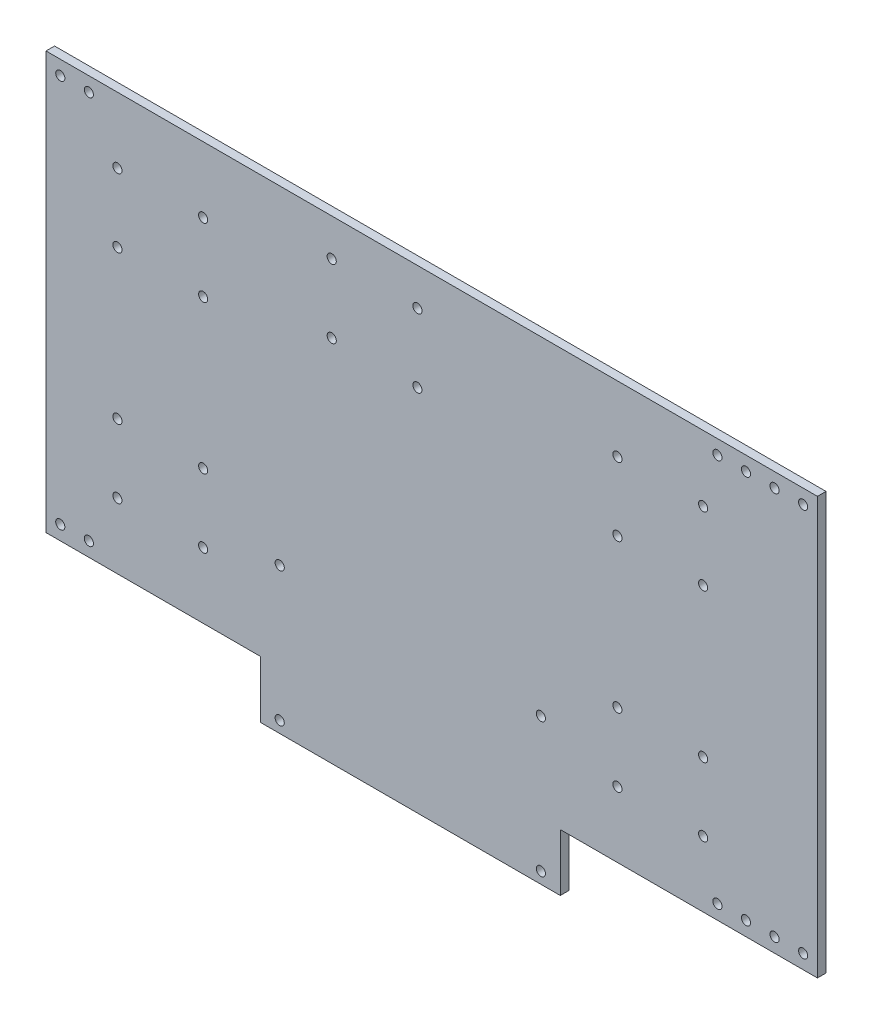
SolidWorks part; units mm, degrees
material "Thornel Mat VMA"
ref_plane "前视基准面" through (0, 0, 0) normal (0, 0, 1) x (1, 0, 0)
ref_plane "上视基准面" through (0, 0, 0) normal (0, 1, 0) x (1, 0, 0)
ref_plane "右视基准面" through (0, 0, 0) normal (1, 0, 0) x (0, 0, -1)
other "Configuration Table"
sketch "草图1" plane through (0, 0, 0) normal (0, 0, 1) x (1, 0, 0)
  line L0 (165.8789, -46.1294) -> (185.8789, -46.1294)
  line L1 (-59.1211, 0.8706) -> (-29.1211, 0.8706) construction
  line L2 (-59.1211, 0.8706) -> (-59.1211, -23.1294) construction
  line L3 (-59.1211, -23.1294) -> (-29.1211, -23.1294) construction
  line L4 (-29.1211, 0.8706) -> (-29.1211, -23.1294) construction
  line L5 (-64.1211, 8.8706) -> (-24.1211, 8.8706) construction
  line L6 (-64.1211, 8.8706) -> (-64.1211, -32.1294) construction
  line L7 (-64.1211, -32.1294) -> (-24.1211, -32.1294) construction
  line L8 (-24.1211, 8.8706) -> (-24.1211, -32.1294) construction
  line L9 (130.8789, -32.1294) -> (130.8789, -73.4635) construction
  line L10 (-79.1211, -46.1294) -> (-9.1211, -46.1294)
  line L13 (-9.1211, -46.1294) -> (-9.1211, -66.1294)
  line L14 (115.8789, 0.8706) -> (145.8789, 0.8706) construction
  line L15 (115.8789, 0.8706) -> (115.8789, -23.1294) construction
  line L16 (115.8789, -23.1294) -> (145.8789, -23.1294) construction
  line L17 (145.8789, 0.8706) -> (145.8789, -23.1294) construction
  line L18 (110.8789, 8.8706) -> (150.8789, 8.8706) construction
  line L19 (110.8789, 8.8706) -> (110.8789, -32.1294) construction
  line L20 (110.8789, -32.1294) -> (150.8789, -32.1294) construction
  line L21 (150.8789, 8.8706) -> (150.8789, -32.1294) construction
  line L22 (95.8789, -46.1294) -> (165.8789, -46.1294)
  line L23 (95.8789, -46.1294) -> (95.8789, -66.1294)
  line L26 (-9.1211, -46.1294) -> (95.8789, -46.1294) construction
  line L27 (-84.1211, 26.8706) -> (185.8789, 26.8706) construction
  line L30 (185.8789, 99.8706) -> (185.8789, -46.1294)
  line L31 (-2.3211, -15.1294) -> (89.0789, -15.1294) construction
  line L32 (-2.3211, -15.1294) -> (-2.3211, -62.1294) construction
  line L33 (-2.3211, -62.1294) -> (89.0789, -62.1294) construction
  line L34 (89.0789, -15.1294) -> (89.0789, -62.1294) construction
  line L35 (-9.1211, -66.1294) -> (95.8789, -66.1294)
  line L41 (-9.1211, 99.8706) -> (95.8789, 99.8706)
  line L42 (150.8789, 44.8706) -> (150.8789, 85.8706) construction
  line L43 (110.8789, 85.8706) -> (150.8789, 85.8706) construction
  line L44 (110.8789, 44.8706) -> (110.8789, 85.8706) construction
  line L45 (110.8789, 44.8706) -> (150.8789, 44.8706) construction
  line L46 (145.8789, 52.8706) -> (145.8789, 76.8706) construction
  line L47 (115.8789, 76.8706) -> (145.8789, 76.8706) construction
  line L48 (115.8789, 52.8706) -> (115.8789, 76.8706) construction
  line L49 (115.8789, 52.8706) -> (145.8789, 52.8706) construction
  line L50 (130.8789, 85.8706) -> (130.8789, 127.2046) construction
  line L51 (-24.1211, 44.8706) -> (-24.1211, 85.8706) construction
  line L52 (-64.1211, 85.8706) -> (-24.1211, 85.8706) construction
  line L53 (-64.1211, 44.8706) -> (-64.1211, 85.8706) construction
  line L54 (-64.1211, 44.8706) -> (-24.1211, 44.8706) construction
  line L55 (-29.1211, 52.8706) -> (-29.1211, 76.8706) construction
  line L56 (-59.1211, 76.8706) -> (-29.1211, 76.8706) construction
  line L57 (-59.1211, 52.8706) -> (-59.1211, 76.8706) construction
  line L58 (-59.1211, 52.8706) -> (-29.1211, 52.8706) construction
  line L59 (165.8789, 99.8706) -> (185.8789, 99.8706)
  line L65 (95.8789, 99.8706) -> (165.8789, 99.8706)
  line L68 (-79.1211, 99.8706) -> (-9.1211, 99.8706)
  line L69 (43.3789, 99.8706) -> (43.3789, -15.1294) construction
  line L78 (30.8789, 94.8706) -> (30.8789, 53.8706) construction
  line L79 (15.8789, 86.8706) -> (45.8789, 86.8706) construction
  line L80 (15.8789, 86.8706) -> (15.8789, 62.8706) construction
  line L81 (15.8789, 62.8706) -> (45.8789, 62.8706) construction
  line L82 (45.8789, 86.8706) -> (45.8789, 62.8706) construction
  line L83 (10.8789, 94.8706) -> (50.8789, 94.8706) construction
  line L84 (10.8789, 94.8706) -> (10.8789, 53.8706) construction
  line L85 (50.8789, 94.8706) -> (50.8789, 53.8706) construction
  line L86 (50.8789, 53.8706) -> (10.8789, 53.8706) construction
  line L87 (-79.1211, -46.1294) -> (-79.1211, 99.8706) construction
  line L88 (-79.1211, 99.8706) -> (-84.1211, 99.8706)
  line L90 (-84.1211, -46.1294) -> (-79.1211, -46.1294)
  line L91 (165.8789, -46.1294) -> (165.8789, 99.8706) construction
  line L92 (-9.1211, 99.8706) -> (-9.1211, 26.8706) construction
  line L93 (95.8789, 99.8706) -> (95.8789, 26.8706) construction
  line L94 (-84.1211, -46.1294) -> (-84.1211, 99.8706)
  line L95 (-79.1211, -41.1294) -> (-69.1211, -41.1294) construction
  circle A0 centre (-59.1211, 0.8706) radius 1.6
  circle A1 centre (-29.1211, 0.8706) radius 1.6
  circle A2 centre (-59.1211, -23.1294) radius 1.6
  circle A3 centre (-29.1211, -23.1294) radius 1.6
  circle A4 centre (115.8789, 0.8706) radius 1.6
  circle A5 centre (145.8789, 0.8706) radius 1.6
  circle A6 centre (115.8789, -23.1294) radius 1.6
  circle A7 centre (145.8789, -23.1294) radius 1.6
  circle A8 centre (-2.3211, -62.1294) radius 1.6
  circle A9 centre (-2.3211, -15.1294) radius 1.6
  circle A10 centre (89.0789, -15.1294) radius 1.6
  circle A11 centre (89.0789, -62.1294) radius 1.6
  circle A16 centre (145.8789, 76.8706) radius 1.6
  circle A17 centre (115.8789, 76.8706) radius 1.6
  circle A18 centre (145.8789, 52.8706) radius 1.6
  circle A19 centre (115.8789, 52.8706) radius 1.6
  circle A20 centre (-29.1211, 76.8706) radius 1.6
  circle A21 centre (-59.1211, 76.8706) radius 1.6
  circle A22 centre (-29.1211, 52.8706) radius 1.6
  circle A23 centre (-59.1211, 52.8706) radius 1.6
  circle A36 centre (15.8789, 86.8706) radius 1.6
  circle A37 centre (45.8789, 86.8706) radius 1.6
  circle A38 centre (15.8789, 62.8706) radius 1.6
  circle A39 centre (45.8789, 62.8706) radius 1.6
  circle A40 centre (-79.1211, -41.1294) radius 1.6
  circle A41 centre (-69.1211, -41.1294) radius 1.6
  circle A42 centre (-79.1211, 94.8706) radius 1.6
  circle A43 centre (-69.1211, 94.8706) radius 1.6
  point P12 (-44.1211, 8.8706)
  point P13 (-44.1211, 0.8706)
  point P33 (130.8789, 8.8706)
  point P34 (130.8789, 0.8706)
  point P54 (43.3789, -62.1294)
  point P55 (43.3789, -46.1294)
  point P80 (-44.1211, -23.1294)
  point P81 (-44.1211, -46.1294)
  point P82 (130.8789, -23.1294)
  point P83 (130.8789, -46.1294)
  point P153 (30.8789, 94.8706)
  point P154 (30.8789, 86.8706)
  dimension "D3" = 3.2
  dimension "D13" = 3.2
  dimension "D22" = 3.2
  dimension "D41" = 3.2
  dimension "D17" = 5
  dimension "D27" = 3.2
  dimension "D1" = 30
  dimension "D2" = 24
  dimension "D4" = 40
  dimension "D5" = 41
  dimension "D6" = 8
  dimension "D7" = 16
  dimension "D8" = 4
  dimension "D9" = 5
  dimension "D10" = 14
  dimension "D11" = 30
  dimension "D12" = 24
  dimension "D14" = 40
  dimension "D15" = 41
  dimension "D16" = 8
  dimension "D18" = 20
  dimension "D19" = 10
  dimension "D20" = 14
  dimension "D21" = 105
  dimension "D23" = 20
  dimension "D24" = 91.4
  dimension "D25" = 47
  dimension "D26" = 5
  dimension "D28" = 146
  dimension "D33" = 14
  dimension "D34" = 14
  dimension "D39" = 30
  dimension "D40" = 24
  dimension "D42" = 40
  dimension "D43" = 41
  dimension "D44" = 8
extrude "凸台-拉伸1" add sketch "草图1" along normal blind 3
sketch "草图4" plane through (0, 0, 3) normal (0, 0, 1) x (1, 0, 0)
  line L0 (170.8789, -41.1294) -> (180.8789, -41.1294)
  line L1 (185.8789, -46.1294) -> (185.8789, 99.8706) construction
  line L2 (95.8789, -46.1294) -> (185.8789, -46.1294) construction
  line L3 (185.8789, 26.8706) -> (-84.1211, 26.8706) construction
  line L4 (160.8789, -41.1294) -> (170.8789, -41.1294) construction
  line L5 (-84.1211, 99.8706) -> (-84.1211, -46.1294) construction
  circle A0 centre (170.8789, -41.1294) radius 1.6
  circle A1 centre (180.8789, -41.1294) radius 1.6
  circle A2 centre (180.8789, 94.8706) radius 1.6
  circle A3 centre (170.8789, 94.8706) radius 1.6
  circle A4 centre (160.8789, -41.1294) radius 1.6
  circle A5 centre (150.8789, -41.1294) radius 1.6
  circle A6 centre (160.8789, 94.8706) radius 1.6
  circle A7 centre (150.8789, 94.8706) radius 1.6
  point P22 (165.8789, -41.1294)
  dimension "D1" = 10
  dimension "D2" = 3.2
  dimension "D5" = 10
  dimension "D3" = 5
  dimension "D4" = 5
  dimension "D6" = 10
  dimension "D7" = 250
extrude "切除-拉伸1" cut sketch "草图4" against normal through all contours A3 | A2 | A0 | A1 | A5 | A4 | A7 | A6
